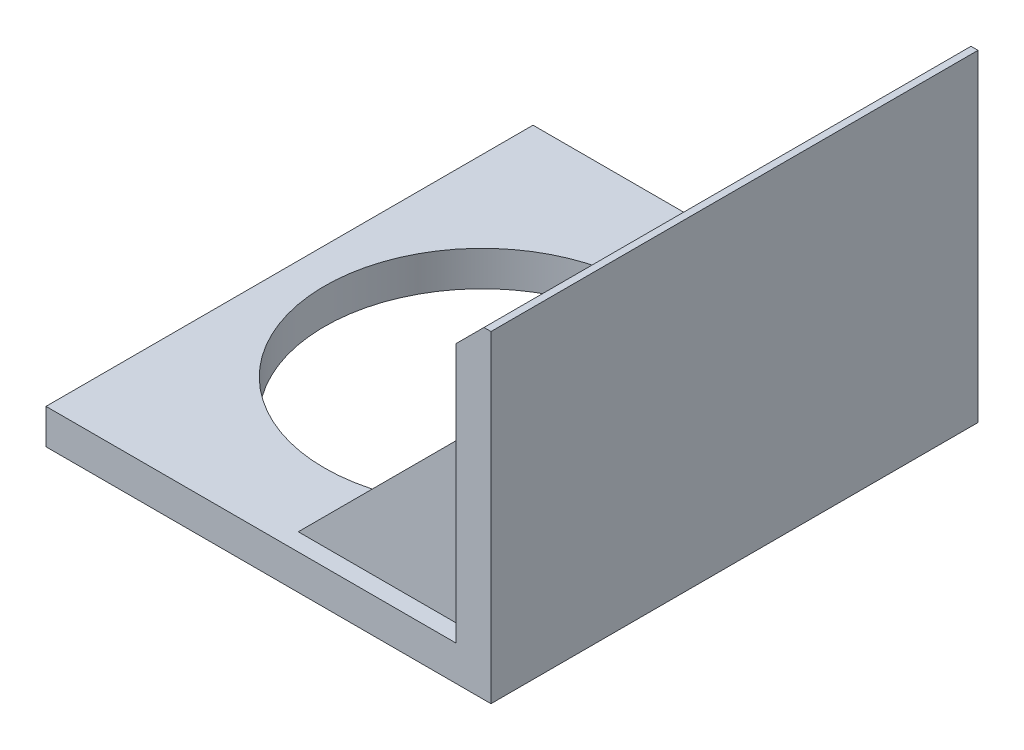
SolidWorks part; units mm, degrees
material "C40 or 38NiCrMo4"
ref_plane "Piano frontale" through (0, 0, 0) normal (0, 0, 1) x (1, 0, 0)
ref_plane "Piano superiore" through (0, 0, 0) normal (0, 1, 0) x (1, 0, 0)
ref_plane "Piano destro" through (0, 0, 0) normal (1, 0, 0) x (0, 0, -1)
sketch "Sketch1" plane through (0, 0, 0) normal (0, 1, 0) x (1, 0, 0)
  line L0 (-1000, 0) -> (49000, 0) construction
  line L1 (0, -1000) -> (0, 49000) construction
  line L2 (0, 69.5) -> (-55, 69.5)
  line L3 (-55, 69.5) -> (-55, -69.5)
  line L4 (0, -69.5) -> (-55, -69.5)
  line L5 (0, 69.5) -> (72, 69.5)
  line L6 (72, 69.5) -> (72, -69.5)
  line L7 (0, -69.5) -> (72, -69.5)
  circle A0 centre (0, 0) radius 45
  point P11 (-55, 0)
  point P15 (72, 0)
  dimension "D1" = 90
  dimension "D2" = 69.5
  dimension "D3" = 55
  dimension "D4" = 72
extrude "Extrude1" add sketch "Sketch1" along normal blind 10
sketch "Sketch2" plane through (0, 10, 0) normal (0, 1, 0) x (1, 0, 0)
  line L1 (72, 69.5) -> (62, 69.5)
  line L2 (72, 69.5) -> (72, -69.5)
  line L3 (72, -69.5) -> (62, -69.5)
  line L4 (62, 69.5) -> (62, -69.5)
  line L5 (-55, -69.5) -> (72, -69.5) construction
  dimension "D1" = 139
  dimension "D2" = 10
extrude "Extrude2" add sketch "Sketch2" along normal blind 82
chamfer "Chamfer1" distance 8 angle 45 1 edges at (62, 92, 0)
sketch "Sketch3" plane through (0, 0, 69.5) normal (0, 0, 1) x (1, 0, 0)
  line L0 (12, 10) -> (62, 10)
  line L1 (-55, 10) -> (62, 10) construction
  line L2 (62, 10) -> (62, 60)
  line L3 (62, 84) -> (62, 10) construction
  line L4 (62, 60) -> (12, 10)
  dimension "D1" = 50
  dimension "D2" = 50
extrude "Extrude3" add sketch "Sketch3" against normal blind 8 from offset 5 offset against normal yes
pattern_linear "LPattern1" count 2 spacing 121 along (0, 0, -1) of "Extrude3"
